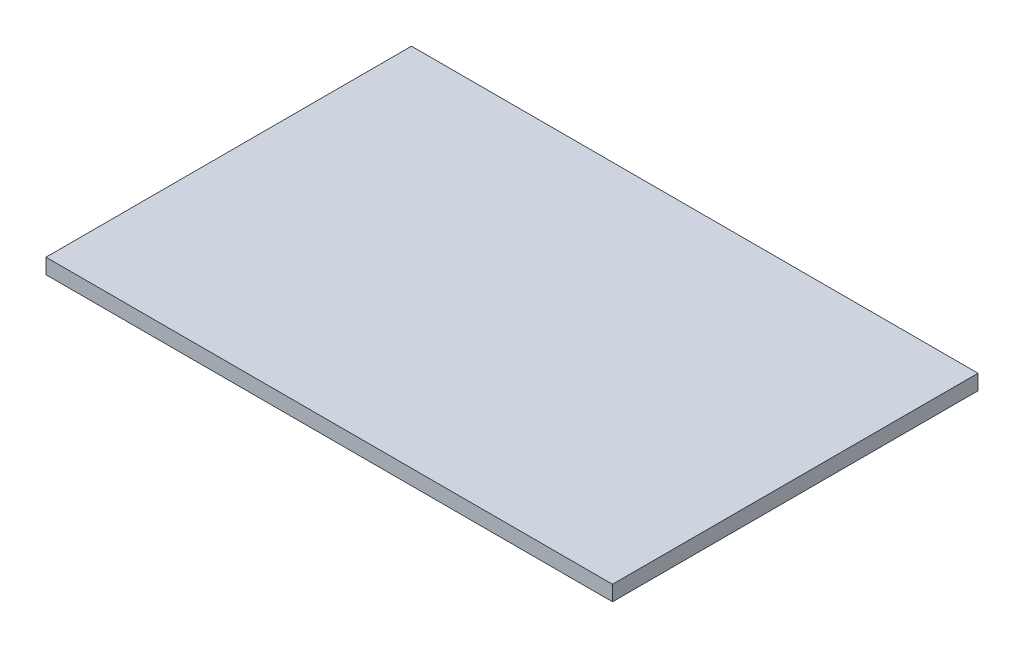
SolidWorks part; units mm, degrees
ref_plane "Front Plane" through (0, 0, 0) normal (0, 0, 1) x (1, 0, 0)
ref_plane "Top Plane" through (0, 0, 0) normal (0, 1, 0) x (1, 0, 0)
ref_plane "Right Plane" through (0, 0, 0) normal (1, 0, 0) x (0, 0, -1)
sketch "Sketch1" plane through (0, 0, 0) normal (0, 1, 0) x (1, 0, 0)
  line L1 (0, 0) -> (186, 0)
  line L2 (0, 0) -> (0, 120)
  line L3 (0, 120) -> (186, 120)
  line L4 (186, 0) -> (186, 120)
  dimension "D1" = 120
  dimension "D2" = 186
extrude "Boss-Extrude1" add sketch "Sketch1" along normal blind 5
